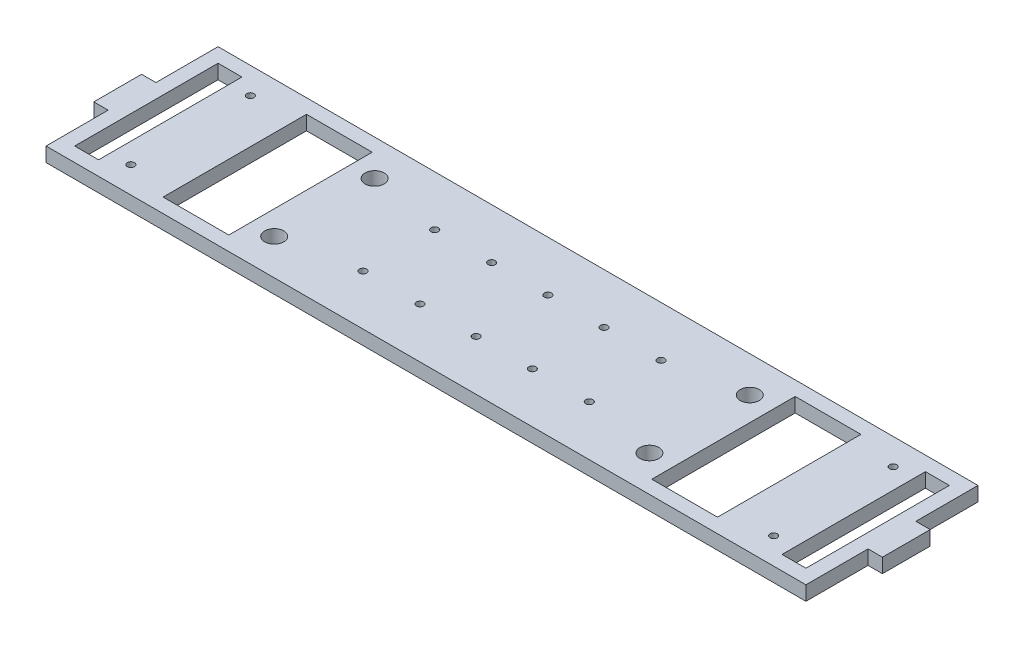
SolidWorks part; units mm, degrees
ref_plane "Plan de face" through (0, 0, 0) normal (0, 0, 1) x (1, 0, 0)
ref_plane "Plan de dessus" through (0, 0, 0) normal (0, 1, 0) x (1, 0, 0)
ref_plane "Plan de droite" through (0, 0, 0) normal (1, 0, 0) x (0, 0, -1)
sketch "Esquisse1" plane through (0, 0, 0) normal (0, 1, 0) x (1, 0, 0)
  line L0 (-159, -36) -> (-159, -10)
  line L1 (-159, 36) -> (159, 36)
  line L2 (-165, -10) -> (-165, 10)
  line L3 (-159, -36) -> (159, -36)
  line L4 (-159, -36) -> (159, 36) construction
  line L5 (159, -36) -> (159, -10)
  line L6 (159, -10) -> (165, -10)
  line L7 (-159, -10) -> (-165, -10)
  line L8 (-165, 10) -> (-159, 10)
  line L9 (-159, 10) -> (-159, 36)
  line L10 (165, -10) -> (165, 10)
  line L11 (165, 10) -> (159, 10)
  line L12 (159, 10) -> (159, 36)
  line L13 (159, 36) -> (159.1702, 35.852) construction
  line L14 (165, 0) -> (-165, 0) construction
  point P0 (0, 0)
  dimension "D1" = 330
  dimension "D2" = 6
  dimension "D3" = 6
  dimension "D4" = 6
  dimension "D5" = 6
  dimension "D6" = 72
  dimension "D7" = 20
  dimension "D8" = 20
extrude "Boss.-Extru.1" add sketch "Esquisse1" along normal blind 6 contours L3 L5 L6 L10 L11 L12 L1 L9 L8 L2 L7 L0
sketch "Esquisse2" plane through (0, 0, 0) normal (0, -1, 0) x (1, 0, 0)
  line L0 (-47.35, 0) -> (47.35, 0) construction
  line L1 (0, 36) -> (0, -36) construction
  line L2 (-47.35, 15) -> (47.35, 15) construction
  line L3 (159, 36) -> (-159, 36) construction
  line L4 (-159, -36) -> (159, -36) construction
  circle A0 centre (-47.35, 15) radius 1.5
  circle A1 centre (-23.5, 15) radius 1.5
  circle A2 centre (23.5, 15) radius 1.5
  circle A3 centre (47.35, 15) radius 1.5
  circle A4 centre (47.35, -15) radius 1.5
  circle A5 centre (23.5, -15) radius 1.5
  circle A6 centre (-23.5, -15) radius 1.5
  circle A7 centre (-47.35, -15) radius 1.5
  circle A8 centre (0, 15) radius 1.5
  circle A9 centre (0, -15) radius 1.5
  dimension "D1" = 3
  dimension "D2" = 3
  dimension "D5" = 3
  dimension "D3" = 23.5
  dimension "D4" = 15
  dimension "D6" = 23.85
extrude "Enlèv. mat.-Extru.1" cut sketch "Esquisse2" against normal through all
sketch "Esquisse3" plane through (0, 0, 0) normal (0, -1, 0) x (-1, 0, 0)
  line L0 (0, -36) -> (0, 36) construction
  line L1 (159, -36) -> (-159, -36) construction
  line L2 (159, 36) -> (-159, 36) construction
  line L3 (165, 0) -> (-165, 0) construction
  line L4 (165, -10) -> (165, 10) construction
  line L5 (-165, -10) -> (-165, 10) construction
  circle A0 centre (47.35, -15) radius 3
  circle A1 centre (23.5, -15) radius 3
  circle A2 centre (0, -15) radius 3
  circle A3 centre (0, 15) radius 3
  circle A4 centre (23.5, 15) radius 3
  circle A5 centre (47.35, 15) radius 3
  circle A6 centre (-47.35, 15) radius 3
  circle A7 centre (-23.5, 15) radius 3
  circle A8 centre (-23.5, -15) radius 3
  circle A9 centre (-47.35, -15) radius 3
  dimension "D1" = 6
  dimension "D2" = 6
  dimension "D3" = 6
extrude "Enlèv. mat.-Extru.2" cut sketch "Esquisse3" against normal blind 3
sketch "Esquisse4" plane through (0, 0, 0) normal (0, -1, 0) x (-1, 0, 0)
  line L0 (165, 0) -> (-165, 0) construction
  line L1 (165, -10) -> (165, 10) construction
  line L2 (-165, -10) -> (-165, 10) construction
  line L4 (159, -36) -> (-159, -36) construction
  line L5 (0, -36) -> (0, 36) construction
  line L6 (159, 36) -> (-159, 36) construction
  circle A0 centre (78.5, -21) radius 4
  circle A1 centre (-78.5, -21) radius 4
  circle A2 centre (78.5, 21) radius 4
  circle A3 centre (-78.5, 21) radius 4
  dimension "D1" = 21
  dimension "D2" = 8
  dimension "D3" = 78.5
extrude "Enlèv. mat.-Extru.3" cut sketch "Esquisse4" against normal through all
sketch "Esquisse5" plane through (0, 0, 0) normal (0, -1, 0) x (-1, 0, 0)
  line L0 (0, -36) -> (0, 36) construction
  line L1 (159, -36) -> (-159, -36) construction
  line L2 (159, 36) -> (-159, 36) construction
  line L3 (-116, 30) -> (-88.5, -30) construction
  line L4 (116, -30) -> (88.5, -30)
  line L5 (116, -30) -> (116, 30)
  line L6 (116, 30) -> (88.5, 30)
  line L7 (88.5, -30) -> (88.5, 30)
  line L8 (116, -30) -> (88.5, 30) construction
  line L9 (116, 30) -> (88.5, -30) construction
  line L10 (-116, -30) -> (-88.5, 30) construction
  line L11 (-88.5, -30) -> (-88.5, 30)
  line L12 (-116, 30) -> (-88.5, 30)
  line L13 (-116, -30) -> (-116, 30)
  line L14 (-116, -30) -> (-88.5, -30)
  point P6 (102.25, 0)
  point P16 (-102.25, 0)
  dimension "D1" = 88.5
  dimension "D2" = 27.5
  dimension "D3" = 60
extrude "Enlèv. mat.-Extru.4" cut sketch "Esquisse5" against normal through all
sketch "Esquisse6" plane through (0, 0, 0) normal (0, -1, 0) x (-1, 0, 0)
  line L0 (0, -36) -> (0, 36) construction
  line L1 (159, -36) -> (-159, -36) construction
  line L2 (159, 36) -> (-159, 36) construction
  line L4 (-165, -10) -> (-165, 10) construction
  line L5 (-165, 0) -> (165, 0) construction
  line L6 (165, -10) -> (165, 10) construction
  circle A0 centre (134.5, -25) radius 1.5
  circle A1 centre (-134.5, -25) radius 1.5
  circle A2 centre (-134.5, 25) radius 1.5
  circle A3 centre (134.5, 25) radius 1.5
  dimension "D1" = 3
  dimension "D2" = 134.5
  dimension "D3" = 25
extrude "Enlèv. mat.-Extru.5" cut sketch "Esquisse6" against normal through all
sketch "Esquisse7" plane through (0, 0, 0) normal (0, -1, 0) x (-1, 0, 0)
  line L0 (0, -36) -> (0, 36) construction
  line L1 (153, -30) -> (143, -30)
  line L2 (153, -30) -> (153, 30)
  line L3 (153, 30) -> (143, 30)
  line L4 (143, -30) -> (143, 30)
  line L5 (153, -30) -> (143, 30) construction
  line L6 (153, 30) -> (143, -30) construction
  line L7 (159, -36) -> (-159, -36) construction
  line L8 (159, 36) -> (-159, 36) construction
  line L9 (-153, 30) -> (-143, -30) construction
  line L10 (-153, -30) -> (-143, 30) construction
  line L11 (-143, -30) -> (-143, 30)
  line L12 (-153, 30) -> (-143, 30)
  line L13 (-153, -30) -> (-153, 30)
  line L14 (-153, -30) -> (-143, -30)
  point P0 (148, 0)
  point P16 (-148, 0)
  dimension "D1" = 143
  dimension "D2" = 10
  dimension "D3" = 60
extrude "Enlèv. mat.-Extru.6" cut sketch "Esquisse7" against normal through all
sketch "Esquisse8" plane through (0, 0, 0) normal (0, -1, 0) x (1, 0, 0)
  line L0 (0, 36) -> (0, -36) construction
  line L1 (-159, 36) -> (159, 36) construction
  line L2 (-159, -36) -> (159, -36) construction
  circle A0 centre (-134.5, 25) radius 3
  circle A1 centre (-134.5, -25) radius 3
  circle A2 centre (134.5, -25) radius 3
  circle A3 centre (134.5, 25) radius 3
  dimension "D1" = 6
  dimension "D2" = 6
extrude "Enlèv. mat.-Extru.7" cut sketch "Esquisse8" against normal blind 3
sketch "Esquisse9" plane through (0, 0, 0) normal (0, -1, 0) x (-1, 0, 0)
  line L1 (117.5, -32.5) -> (-117.5, -32.5) construction
  line L2 (117.5, -32.5) -> (117.5, 32.5) construction
  line L3 (117.5, 32.5) -> (-117.5, 32.5) construction
  line L4 (-117.5, -32.5) -> (-117.5, 32.5) construction
  line L5 (117.5, -32.5) -> (-117.5, 32.5) construction
  line L6 (117.5, 32.5) -> (-117.5, -32.5) construction
  line L7 (-144.5, -32.5) -> (-124.5, -32.5)
  line L8 (-144.5, -32.5) -> (-144.5, 32.5)
  line L9 (-144.5, 32.5) -> (-124.5, 32.5)
  line L10 (-124.5, -32.5) -> (-124.5, 32.5)
  line L11 (-144.5, -32.5) -> (-124.5, 32.5) construction
  line L12 (-144.5, 32.5) -> (-124.5, -32.5) construction
  circle A0 centre (-134.5, -25) radius 1.5
  circle A1 centre (-134.5, 25) radius 1.5
  point P0 (0, 0)
  point P5 (-134.5, 0)
  point P17 (-137.4108, -17.9402)
  dimension "D5" = 3
  dimension "D6" = 3
  dimension "D1" = 235
  dimension "D2" = 65
  dimension "D3" = 20
  dimension "D4" = 7
  dimension "D7" = 50
  dimension "D8" = 25
